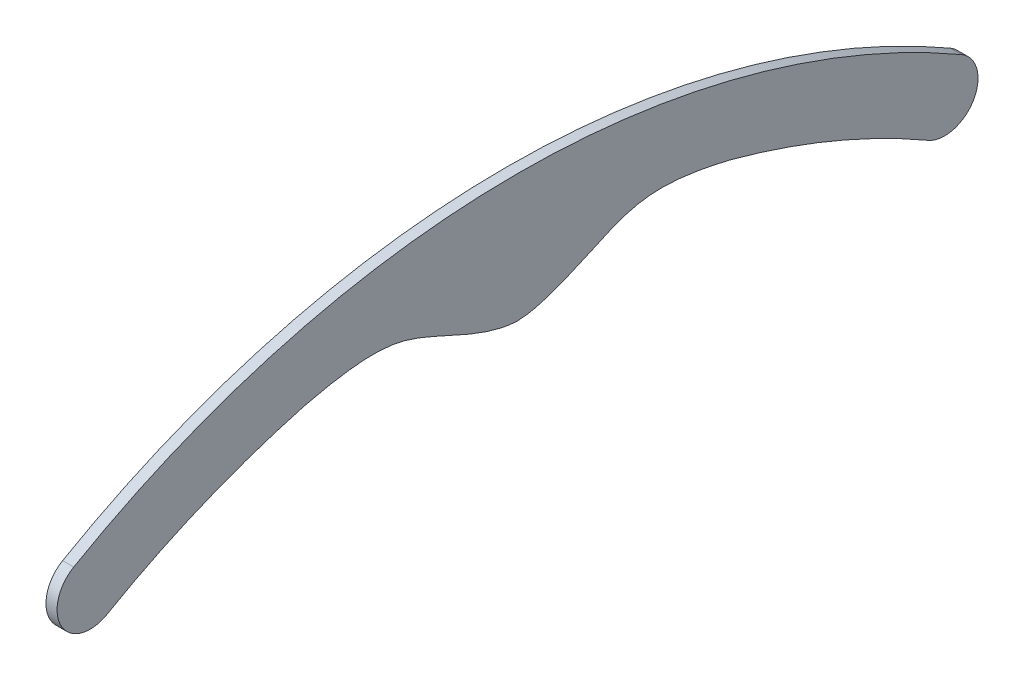
SolidWorks part; units mm, degrees
ref_plane "Plano frontal" through (0, 0, 0) normal (1, 0, 0) x (0, 1, 0)
ref_plane "Plano superior" through (0, 0, 0) normal (0, 0, 1) x (0, 1, 0)
ref_plane "Plano direito" through (0, 0, 0) normal (0, 1, 0) x (-1, 0, 0)
sketch "Esboço1" plane through (0, 0, 0) normal (1, 0, 0) x (0, 1, 0)
  line L0 (307.6746, 0) -> (550.5735, 0) construction
  line L1 (550.5735, 0) -> (67.0307, 0) construction
  line L2 (266.5509, 60.5772) -> (266.5509, -122.8485) construction
  line L3 (377.5509, -142.0589) -> (377.5509, 120.4468) construction
  line L4 (266.5509, -122.8485) -> (266.5509, 103.3766) construction
  line L5 (362.5509, -142.0589) -> (362.5509, 120.4468) construction
  line L8 (351.3744, 10.2425) -> (357.8715, 7.2783) construction
  line L9 (351.3921, 10.2337) -> (299.7965, 35.8323) construction
  line L10 (351.3744, -10.2425) -> (357.8715, -7.2783) construction
  arc A0 (350.756, -100) -> (350.756, 100) centre (177.5509, 0) ccw
  arc A2 (337.7656, -92.5) -> (356.2386, -47.9133) centre (177.5509, 0) ccw
  arc A3 (350.756, -100) -> (337.7656, -92.5) centre (344.2608, -96.25) cw
  circle A5 centre (266.5509, 0) radius 14 construction
  arc A6 (356.2386, 47.9133) -> (337.7656, 92.5) centre (177.5509, 0) ccw
  arc A7 (357.8715, 7.2783) -> (357.8715, -7.2783) centre (354.5509, 0) cw construction
  arc A8 (337.7656, 92.5) -> (350.756, 100) centre (344.2608, 96.25) cw
  spline S0 degree 3 poles (356.2386, 47.9133) (360.346, 30.9055) (357.1089, 22.6327) (348.8644, 5.2789) (348.7857, 0) knots 0.097243 0.097243 0.097243 0.097243 0.646678 1 1 1 1
  spline S1 degree 3 poles (356.2386, -47.9133) (360.346, -30.9055) (357.1089, -22.6327) (348.8644, -5.2789) (348.7857, 0) knots 0.097243 0.097243 0.097243 0.097243 0.646678 1 1 1 1
  point P31 (362.5509, 0)
  dimension "D3" = 200
  dimension "D2" = 100
  dimension "D5" = 15
extrude "Ressalto-extrusão1" add sketch "Esboço1" along normal blind 2.5
